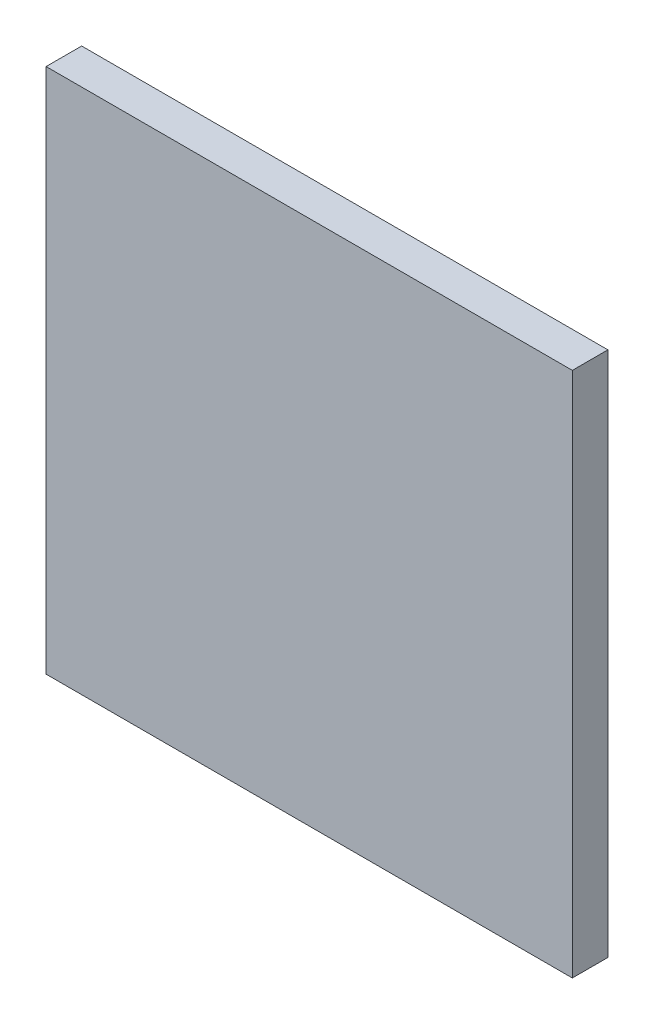
SolidWorks part; units mm, degrees
ref_plane "Alzado" through (0, 0, 0) normal (0, 0, 1) x (1, 0, 0)
ref_plane "Planta" through (0, 0, 0) normal (0, 1, 0) x (1, 0, 0)
ref_plane "Vista lateral" through (0, 0, 0) normal (1, 0, 0) x (0, 0, -1)
sketch "Croquis1" plane through (0, 0, 0) normal (0, 0, 1) x (1, 0, 0)
  line L0 (227.2469, 511.3055) -> (1136.2343, 511.3055) construction
  line L1 (605.1234, 694.282) -> (975.1234, 694.282)
  line L2 (975.1234, 694.282) -> (975.1234, 324.282)
  line L3 (975.1234, 324.282) -> (605.1234, 324.282)
  line L4 (605.1234, 324.282) -> (605.1234, 694.282)
  line L5 (0, 0) -> (605.1234, 0) construction
  line L6 (605.1234, 0) -> (605.1234, 324.282) construction
  dimension "D1" = 370
  dimension "D2" = 370
extrude "Saliente-Extruir1" add sketch "Croquis1" along normal blind 25 contours L2 L3 L4 L1
